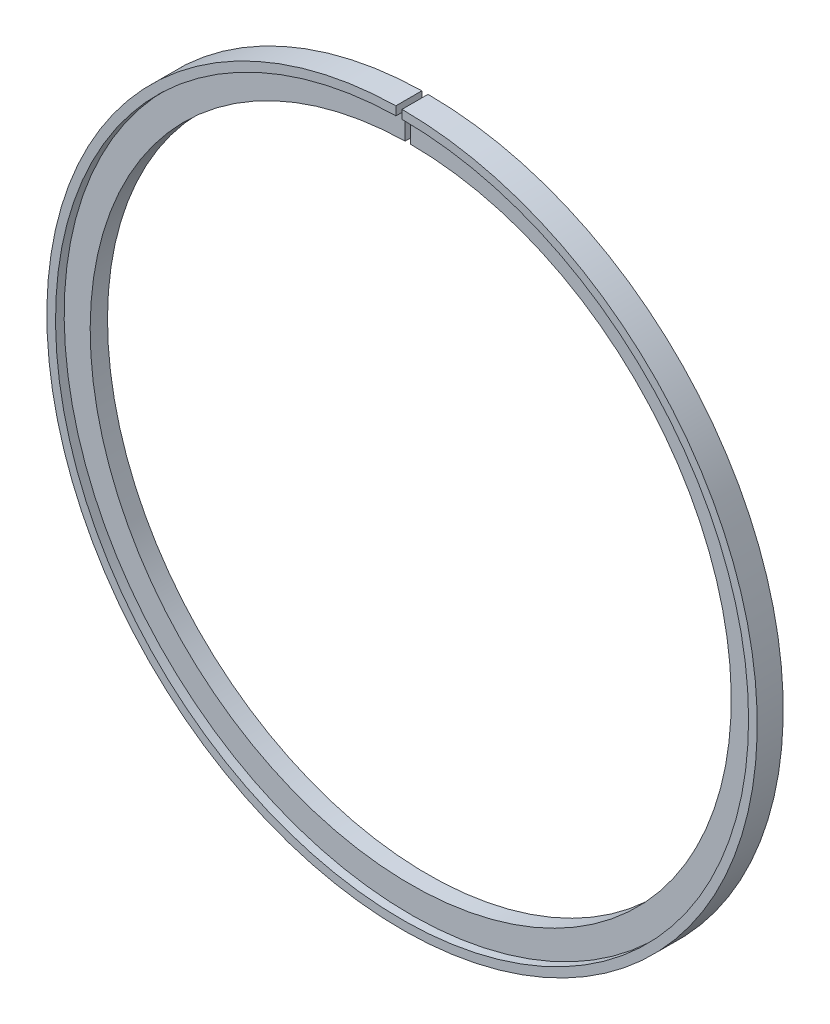
SolidWorks part; units mm, degrees
ref_plane "前视基准面" through (0, 0, 0) normal (0, 0, 1) x (1, 0, 0)
ref_plane "上视基准面" through (0, 0, 0) normal (0, 1, 0) x (1, 0, 0)
ref_plane "右视基准面" through (0, 0, 0) normal (1, 0, 0) x (0, 0, -1)
other "Configuration Table"
sketch "草图1" plane through (0, 0, 0) normal (0, 0, 1) x (1, 0, 0)
  line L2 (0, 0) -> (49.7545, 0) construction
  line L3 (49.7545, 0) -> (-51.965, 0) construction
  line L4 (-0.6457, 36.9944) -> (-0.7155, 40.9938)
  line L5 (0, 37) -> (0, 41)
  line L6 (0, 0) -> (0, -45.3567) construction
  line L7 (0, 0) -> (0, 51.6476) construction
  arc A0 (-0.7155, 40.9938) -> (0, 41) centre (0, 0) ccw
  arc A1 (-0.6457, 36.9944) -> (0, 37) centre (0, 0) ccw
  dimension "D1" = 82
  dimension "D2" = 74
  dimension "D3" = 1
  dimension "D4" = 3.9994
  dimension "D5" = 4
extrude "凸台-拉伸1" add sketch "草图1" along normal blind 2
sketch "草图2" plane through (0, 0, 2) normal (0, 0, 1) x (1, 0, 0)
  line L0 (0, 0) -> (-49.1993, 0) construction
  line L1 (-49.1993, 0) -> (50.9076, 0) construction
  line L2 (0, 40) -> (0, 45.7718) construction
  line L3 (0, 45.7718) -> (0, 40) construction
  line L4 (-0.6981, 39.9939) -> (-0.7155, 40.9938)
  line L5 (0, 40) -> (0, 41)
  line L6 (0, 0) -> (0, -45.0083) construction
  line L7 (0, 0) -> (0, 45.7718) construction
  arc A0 (-0.7155, 40.9938) -> (0, 41) centre (0, 0) ccw
  arc A1 (-0.6981, 39.9939) -> (0, 40) centre (0, 0) ccw
  dimension "D1" = 1
  dimension "D2" = 80
extrude "凸台-拉伸3" add sketch "草图2" along normal blind 1
